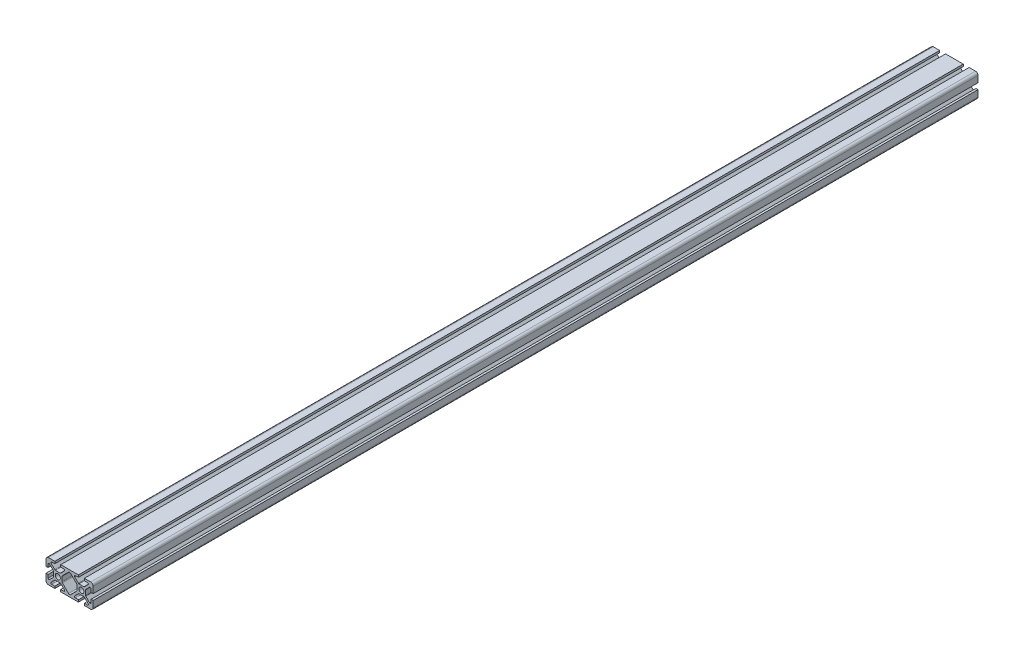
SolidWorks part; units mm, degrees
ref_plane "Front Plane" through (0, 0, 0) normal (0, 0, 1) x (1, 0, 0)
ref_plane "Top Plane" through (0, 0, 0) normal (0, 1, 0) x (1, 0, 0)
ref_plane "Right Plane" through (0, 0, 0) normal (1, 0, 0) x (0, 0, -1)
sketch "Sketch1" plane through (0, 0, 0) normal (0, 0, 1) x (1, 0, 0)
  line L0 (10, 10) -> (10, -10) construction
  line L1 (-20, 0) -> (20, 0) construction
  line L2 (12.5, -10) -> (20, -10)
  line L3 (20, -10) -> (20, -2.5)
  line L4 (12.5, -10) -> (12.5, -8.2134)
  line L5 (12.5, -8.2134) -> (16.95, -8.2134)
  line L6 (16.95, -8.2134) -> (12.3366, -3.6)
  line L7 (10, 0) -> (20, -10) construction
  line L8 (20, -2.5) -> (18.2134, -2.5)
  line L9 (18.2134, -2.5) -> (18.2134, -6.95)
  line L10 (18.2134, -6.95) -> (13.6, -2.3366)
  line L11 (15.9067, -4.6433) -> (14.6433, -5.9067) construction
  line L12 (0, 10) -> (0, -10) construction
  line L13 (0, -10) -> (-20, -10) construction
  line L14 (-10, 10) -> (10, 10) construction
  line L15 (20, 2.5) -> (20, -2.5) construction
  circle A0 centre (10, 0) radius 2.15
  arc A1 (15.5015, -8.2134) -> (15.9257, -7.1891) centre (15.5015, -7.6134) ccw construction
  point P8 (10, -3.6)
  point P16 (15.275, -5.275)
  point P30 (20, 0)
  dimension "Center Hole Diameter" = 4.3
  dimension "D3" = 0.6
  dimension "Rail Width" = 20
  dimension "T-Slot Width" = 5
  dimension "Slot Depth" = 6.4
  dimension "Rail Height" = 40
  dimension "Inner Slot Width" = 13.9
  dimension "Hole Spacing" = 20
sketch "Sketch2" plane through (0, 0, 0) normal (1, 0, 0) x (0, 0, -1)
  line L0 (-375, -10) -> (375, -10) construction
  line L1 (-335, 0) -> (335, 0) construction
  point P6 (-335, 0)
  point P8 (335, 0)
  dimension "Length" = 750
  dimension "D1" = 40
sketch "Sketch3" plane through (0, 0, 0) normal (0, 0, 1) x (1, 0, 0)
  line L0 (12.5, -10) -> (17.9, -10)
  line L1 (12.5, -10) -> (20, -10) construction
  line L2 (12.5, -10) -> (12.5, -8.2134) construction
  line L3 (12.5, -8.2134) -> (16.95, -8.2134) construction
  line L4 (12.5, -8.2134) -> (12.5, -10)
  line L5 (12.5, -8.2134) -> (16.95, -8.2134)
  line L6 (10, -3.6) -> (12.3366, -3.6)
  line L7 (16.95, -8.2134) -> (12.3366, -3.6) construction
  line L8 (12.3366, -3.6) -> (16.95, -8.2134)
  line L9 (20, -10) -> (20, -2.5) construction
  line L10 (18.2134, -6.95) -> (13.6, -2.3366) construction
  line L11 (18.2134, -2.5) -> (18.2134, -6.95) construction
  line L12 (18.2134, -6.95) -> (18.2134, -2.5)
  line L13 (20, -2.5) -> (18.2134, -2.5) construction
  line L14 (18.2134, -2.5) -> (20, -2.5)
  line L15 (20, -2.5) -> (20, -7.9)
  line L16 (18.2134, -6.95) -> (13.6, -2.3366)
  line L17 (13.6, 0) -> (13.6, -2.3366)
  line L18 (-20, 0) -> (20, 0) construction
  line L19 (10, -3.6) -> (10, -2.15)
  line L20 (10, 10) -> (10, -10) construction
  line L21 (13.6, 0) -> (12.15, 0)
  arc A5 (17.9, -10) -> (20, -7.9) centre (17.9, -7.9) ccw
  circle A10 centre (10, 0) radius 2.15 construction
  arc A11 (10, -2.15) -> (12.15, 0) centre (10, 0) ccw
  dimension "D1" = 2.1
extrude "Boss-Extrude1" add sketch "Sketch3" along normal mid plane 750
sketch "Sketch4" plane through (0, 0, 0) normal (0, 0, 1) x (1, 0, 0)
  line L0 (10, -3.6) -> (7.6634, -3.6)
  line L4 (7.6634, -3.6) -> (3.05, -8.2134)
  line L5 (3.05, -8.2134) -> (7.5, -8.2134)
  line L6 (7.5, -8.2134) -> (7.5, -10)
  line L18 (7.5, -10) -> (0, -10)
  line L19 (12.5, -10) -> (12.5, -8.2134) construction
  line L20 (12.5, -8.2134) -> (16.95, -8.2134) construction
  line L21 (10, -3.6) -> (12.3366, -3.6) construction
  line L22 (16.95, -8.2134) -> (12.3366, -3.6) construction
  line L23 (0, -8.7366) -> (6.4, -2.3366)
  line L24 (0, 10) -> (0, -10) construction
  line L25 (6.4, -2.3366) -> (6.4, 0)
  line L26 (-20, 0) -> (20, 0) construction
  line L27 (6.4, 0) -> (7.85, 0)
  line L28 (13.6, 0) -> (12.15, 0) construction
  line L29 (0, -8.7366) -> (0, -10)
  line L30 (10, -2.15) -> (10, -3.6)
  circle A4 centre (10, 0) radius 2.15 construction
  arc A5 (7.85, 0) -> (10, -2.15) centre (10, 0) ccw
extrude "Boss-Extrude2" add sketch "Sketch4" along normal mid plane 750
mirror "Mirror1" about plane through (0, 0, 0) normal (1, 0, 0) of bodies 137 134
mirror "Mirror2" about plane through (0, 0, 0) normal (0, 1, 0) of bodies 135
fillet "Fillet1" radius 0.75 24 edges at (-7.6634, -3.6, 0) (-12.3366, -3.6, 0) (12.3366, -3.6, 0) (7.6634, -3.6, 0) (-3.05, -8.2134, 0) (-18.2134, -6.95, 0) (-16.95, -8.2134, 0) (-13.6, -2.3366, 0) (-18.2134, 6.95, 0) (-16.95, 8.2134, 0) (-12.3366, 3.6, 0) (-7.6634, 3.6, 0) (-3.05, 8.2134, 0) (-13.6, 2.3366, 0) (3.05, 8.2134, 0) (13.6, -2.3366, 0) (13.6, 2.3366, 0) (7.6634, 3.6, 0) (12.3366, 3.6, 0) (16.95, 8.2134, 0) (18.2134, 6.95, 0) (18.2134, -6.95, 0) (16.95, -8.2134, 0) (3.05, -8.2134, 0)
fillet "Fillet2" radius 1.25 6 edges at (0, -8.7366, 0) (-6.4, -2.3366, 0) (-6.4, 2.3366, 0) (6.4, -2.3366, 0) (6.4, 2.3366, 0) (0, 8.7366, 0)
equation "\"D1@Sketch3\" = \"D3@Sketch1\" * 3.5"
equation "\"D1@Boss-Extrude1\" = \"Length@Sketch2\""
equation "\"D1@Boss-Extrude2\" = \"Length@Sketch2\""
equation "\"D1@Sketch2\"=\"Rail Height@Sketch1\""
